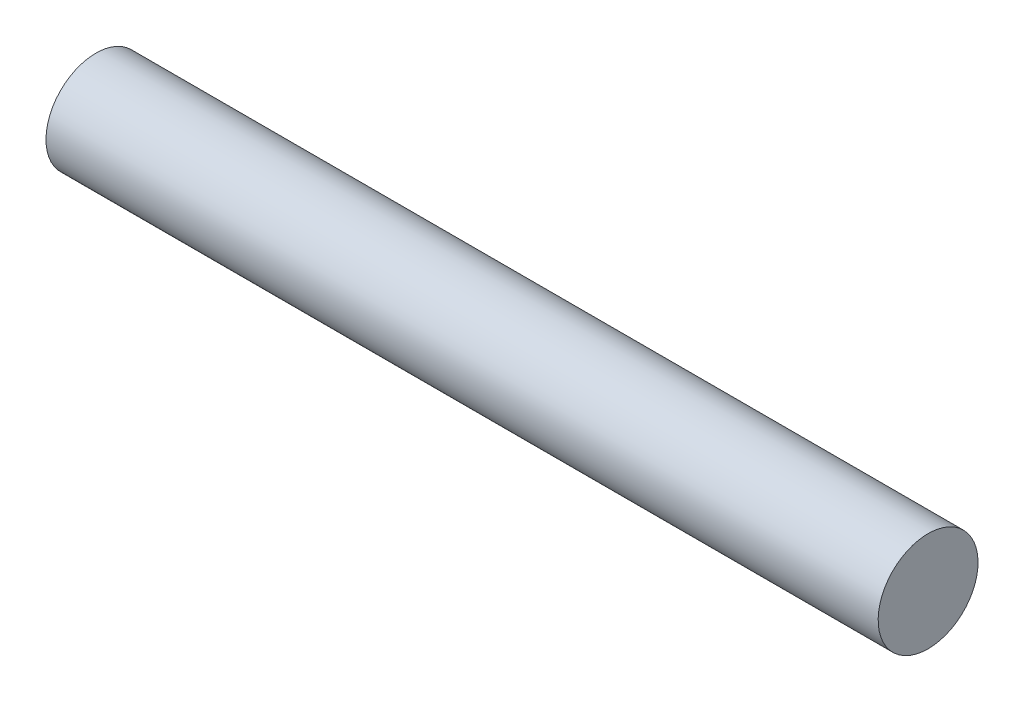
SolidWorks part; units mm, degrees
ref_plane "Ön Düzlem" through (0, 0, 0) normal (0, 0, 1) x (1, 0, 0)
ref_plane "Üst Düzlem" through (0, 0, 0) normal (0, 1, 0) x (1, 0, 0)
ref_plane "Sağ Düzlem" through (0, 0, 0) normal (1, 0, 0) x (0, 0, -1)
sketch "Sketch1" plane through (0, 0, 0) normal (0, 0, 1) x (1, 0, 0)
  line L1 (-138.4938, 8.449) -> (61.5062, 8.449)
  line L2 (-138.4938, 8.449) -> (-138.4938, -3.551)
  line L3 (-138.4938, -3.551) -> (61.5062, -3.551)
  line L4 (61.5062, 8.449) -> (61.5062, -3.551)
  dimension "D1" = 12
  dimension "D2" = 200
revolve "Revolve1" add sketch "Sketch1" angle 360 about L1
